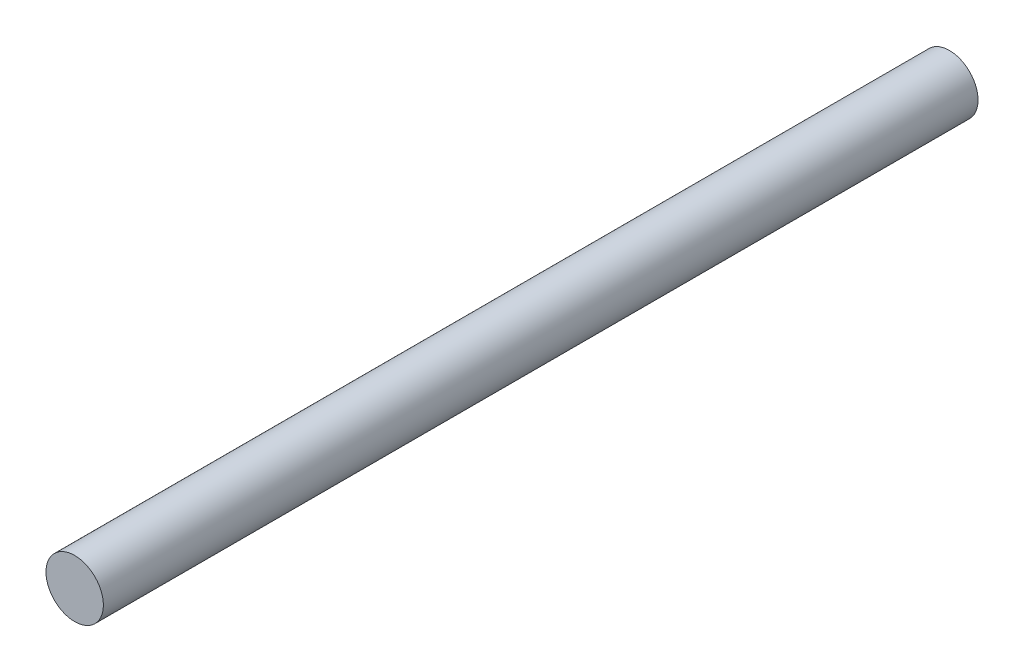
SolidWorks part; units mm, degrees
material "Plain Carbon Steel"
ref_plane "Front Plane" through (0, 0, 0) normal (0, 0, 1) x (1, 0, 0)
ref_plane "Top Plane" through (0, 0, 0) normal (0, 1, 0) x (1, 0, 0)
ref_plane "Right Plane" through (0, 0, 0) normal (1, 0, 0) x (0, 0, -1)
sketch "Sketch1" plane through (0, 0, 0) normal (0, 0, 1) x (1, 0, 0)
  circle A0 centre (0, 0) radius 2
  dimension "D1" = 4
extrude "Boss-Extrude1" add sketch "Sketch1" along normal mid plane 61 contours A0
cosmetic thread "Cosmetic Thread1" parameters "D1"=15, "D2"=3.22
cosmetic thread "Cosmetic Thread2" parameters "D1"=15, "D2"=3.22
